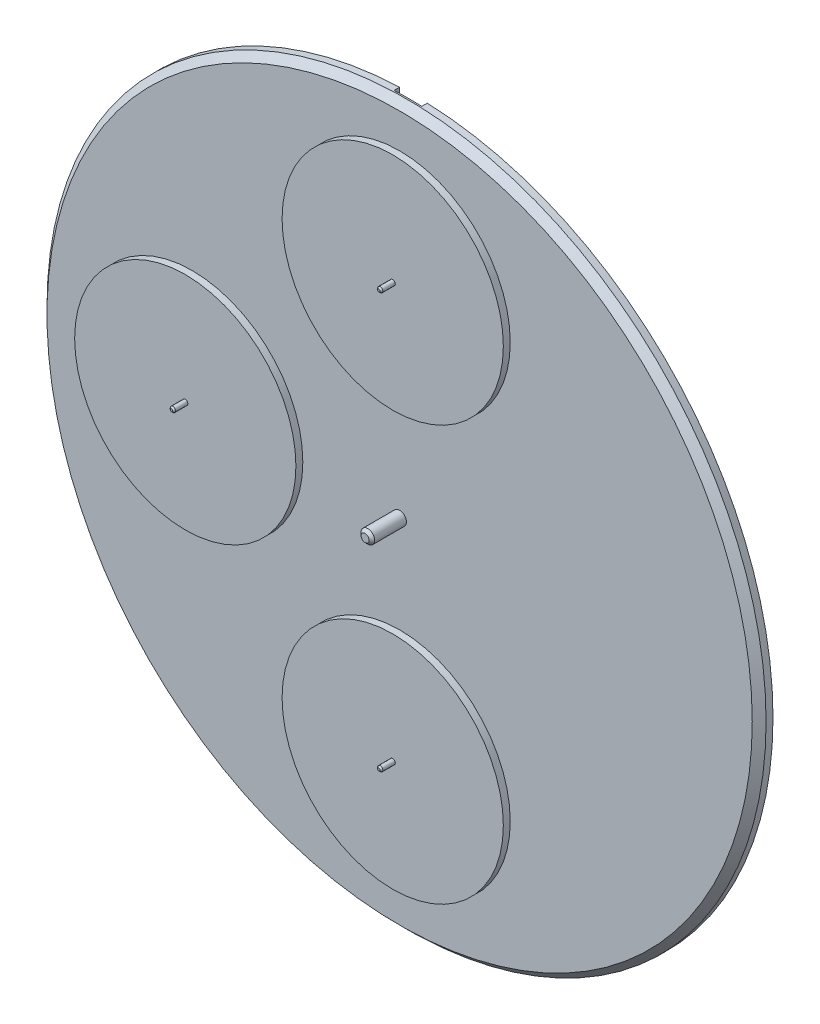
SolidWorks part; units mm, degrees
material "PW110:Md:De:3:20:41:62:"
ref_plane "Front" through (0, 0, 0) normal (0, 0, 1) x (1, 0, 0)
ref_plane "Top" through (0, 0, 0) normal (0, 1, 0) x (1, 0, 0)
ref_plane "Right" through (0, 0, 0) normal (1, 0, 0) x (0, 0, -1)
sketch "Sketch1" plane through (0, 0, 0) normal (0, 0, 1) x (1, 0, 0)
  circle A4 centre (0, 0) radius 13
  dimension "D1" = 26
extrude "Base-Extrude" add sketch "Sketch1" against normal blind 0.5
sketch "Sketch2" plane through (0, 0, 0) normal (0, 0, 1) x (1, 0, 0)
  line L0 (-19.6851, 0) -> (20.2961, 0) construction
  line L1 (0, 17.3189) -> (0, -16.8635) construction
  circle A0 centre (10, 0) radius 1.75 construction
  circle A1 centre (-7.5, 0) radius 4
  circle A2 centre (0, 7.5) radius 4
  circle A3 centre (0, -7.5) radius 4
  point P12 (0, 0)
  dimension "D1" = 8
  dimension "D2" = 8
  dimension "D3" = 8
  dimension "D4" = 3.5
  dimension "D5" = 10
  dimension "D6" = 7.5
  dimension "D7" = 7.5
  dimension "D8" = 7.5
extrude "Boss-Extrude1" add sketch "Sketch2" along normal blind 0.25
sketch "Sketch3" plane through (0, 0, 0) normal (0, 0, 1) x (1, 0, 0)
  circle A0 centre (-7.5, 0) radius 0.0937
  circle A2 centre (0, 7.5) radius 0.0938
  circle A3 centre (0, -7.5) radius 0.0938
  dimension "D1" = 0.1875
  dimension "D2" = 0.1875
  dimension "D3" = 0.1875
extrude "Boss-Extrude2" add sketch "Sketch3" along normal blind 0.75
sketch "Sketch4" plane through (0, 0, 0) normal (0, 0, 1) x (1, 0, 0)
  circle A0 centre (0, 0) radius 0.245
  dimension "D1" = 0.49
extrude "Boss-Extrude3" add sketch "Sketch4" along normal blind 1.25
sketch "Sketch5" plane through (0, 0, -0.5) normal (0, 0, -1) x (-1, 0, 0)
  line L0 (0, 0) -> (0, 10.4664) construction
  line L2 (0.5, 12) -> (-0.5, 12)
  line L3 (0.5, 12) -> (0.5, 14)
  line L4 (0.5, 14) -> (-0.5, 14)
  line L5 (-0.5, 12) -> (-0.5, 14)
  circle A1 centre (0, 0) radius 13
  circle A2 centre (0, 0) radius 13 construction
  point P8 (0, 12)
  dimension "D2" = 12
  dimension "D3" = 2
  dimension "D4" = 1
  dimension "D1" = 0
extrude "Cut-Extrude1" cut sketch "Sketch5" against normal blind 0.2
chamfer "Chamfer1" distance 0.1 angle 45 1 edges at (0.245, 0, 1.25)
chamfer "Chamfer2" distance 0.05 angle 45 3 edges at (-7.4062, 0, 0.75) (0.0938, 7.5, 0.75) (0.0938, -7.5, 0.75)
chamfer "Chamfer4" distance 0.25 angle 45 1 edges at (13, 0, 0)
